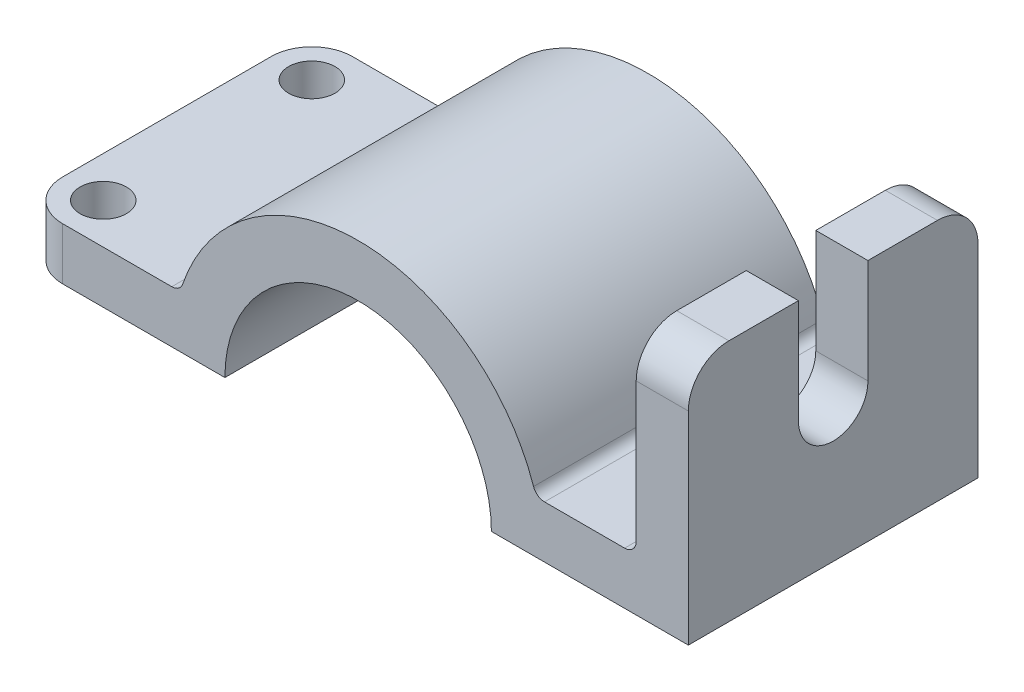
SolidWorks part; units mm, degrees
ref_plane "Front Plane" through (0, 0, 0) normal (0, 0, 1) x (1, 0, 0)
ref_plane "Top Plane" through (0, 0, 0) normal (0, 1, 0) x (1, 0, 0)
ref_plane "Right Plane" through (0, 0, 0) normal (1, 0, 0) x (0, 0, -1)
sketch "Sketch1" plane through (0, 0, 0) normal (0, 0, 1) x (1, 0, 0)
  line L0 (-58, 0) -> (-23, 0)
  line L1 (57, 0) -> (57, 42)
  line L2 (57, 42) -> (48, 42)
  line L3 (48, 42) -> (48, 11)
  line L4 (46, 9) -> (32.1714, 9)
  line L5 (-58, 9) -> (-58, 0)
  line L6 (23, 0) -> (57, 0)
  line L7 (-32.1714, 9) -> (-58, 9)
  arc A0 (30.279, 10.3529) -> (-30.279, 10.3529) centre (0, 0) ccw
  arc A1 (23, 0) -> (-23, 0) centre (0, 0) ccw
  arc A2 (-32.1714, 9) -> (-30.279, 10.3529) centre (-32.1714, 11) ccw
  arc A3 (32.1714, 9) -> (30.279, 10.3529) centre (32.1714, 11) cw
  arc A4 (48, 11) -> (46, 9) centre (46, 11) cw
  dimension "D3" = 46
  dimension "D7" = 2
  dimension "D8" = 32
  dimension "D1" = 115
  dimension "D2" = 57
  dimension "D4" = 9
  dimension "D5" = 42
  dimension "D6" = 9
extrude "Boss-Extrude1" add sketch "Sketch1" along normal mid plane 50
sketch "Sketch2" plane through (57, 0, 0) normal (1, 0, 0) x (0, 0, -1)
  line L0 (0, 24) -> (0, 42) construction
  line L1 (-6, 24) -> (-6, 42)
  line L2 (6, 24) -> (6, 42)
  line L3 (-25, 42) -> (25, 42) construction
  arc A0 (-6, 24) -> (6, 24) centre (0, 24) ccw
  arc A1 (6, 42) -> (-6, 42) centre (0, 42) ccw
  point P3 (0, 33)
  dimension "D1" = 18
  dimension "D2" = 12
extrude "Cut-Extrude1" cut sketch "Sketch2" against normal up to next
fillet "Fillet1" radius 7 2 edges at (52.5, 42, -25) (52.5, 42, 25)
sketch "Sketch3" plane through (0, 9, 0) normal (0, 1, 0) x (1, 0, 0)
  line L0 (-51, 23.9615) -> (-51, -28.2345) construction
  line L1 (-58, -25) -> (-58, 25) construction
  line L2 (-32.1714, 25) -> (-58, 25) construction
  line L3 (-32.1714, -25) -> (-58, -25) construction
  circle A0 centre (-51, 18) radius 4
  circle A1 centre (-51, -18) radius 4
  dimension "D1" = 8
  dimension "D2" = 8
  dimension "D3" = 7
  dimension "D4" = 7
  dimension "D5" = 7
fillet "Fillet2" radius 7 2 edges at (-58, 4.5, 25) (-58, 4.5, -25)
extrude "Cut-Extrude2" cut sketch "Sketch3" against normal up to next
